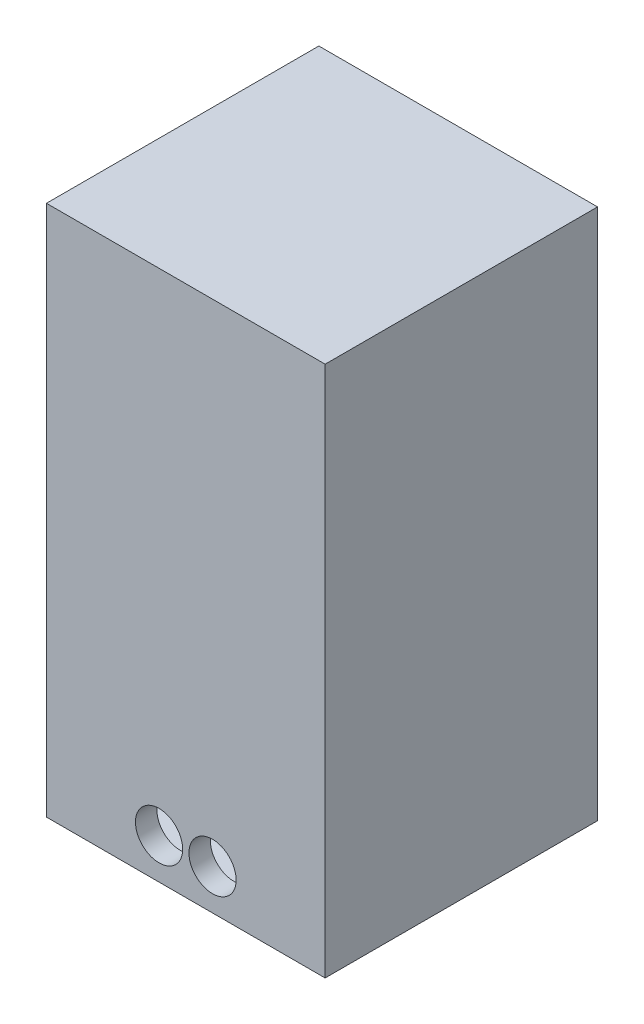
SolidWorks part; units mm, degrees
ref_plane "Front Plane" through (0, 0, 0) normal (0, 0, 1) x (1, 0, 0)
ref_plane "Top Plane" through (0, 0, 0) normal (0, 1, 0) x (1, 0, 0)
ref_plane "Right Plane" through (0, 0, 0) normal (1, 0, 0) x (0, 0, -1)
ref_plane "Plane1" through (0, 0, 433) normal (0, 0, 1) x (1, 0, 0)
sketch "Sketch1" plane through (0, 0, 433) normal (0, 0, 1) x (1, 0, 0)
  line L0 (-443, 1672) -> (-443, -18)
  line L1 (-443, -18) -> (443, -18)
  line L2 (443, -18) -> (443, 1672)
  line L3 (443, 1672) -> (-443, 1672)
  dimension "D1" = 1690
extrude "Boss-Extrude1" add sketch "Sketch1" against normal blind 866
ref_plane "Plane2" through (-425, 0, 0) normal (-1, 0, 0) x (0, -1, 0)
sketch "Sketch2" plane through (-425, 0, 0) normal (-1, 0, 0) x (0, -1, 0)
  line L0 (-7, -415) -> (-7, 415)
  line L1 (-7, 415) -> (-1647, 415)
  line L2 (-1647, 415) -> (-1647, -415)
  line L3 (-1647, -415) -> (-7, -415)
  dimension "D1" = 1640
extrude "Cut-Extrude1" cut sketch "Sketch2" against normal blind 850
sketch "Sketch3" plane through (0, 0, -433) normal (0, 0, -1) x (-1, 0, 0)
  line L0 (-300, 1615) -> (-300, 1605)
  line L1 (-285, 1590) -> (285, 1590)
  line L2 (300, 1605) -> (300, 1615)
  line L3 (285, 1630) -> (-285, 1630)
  arc A0 (-300, 1605) -> (-285, 1590) centre (-285, 1605) ccw
  arc A1 (285, 1590) -> (300, 1605) centre (285, 1605) ccw
  arc A2 (300, 1615) -> (285, 1630) centre (285, 1615) ccw
  arc A3 (-285, 1630) -> (-300, 1615) centre (-285, 1615) ccw
  dimension "D1" = 1590
extrude "Cut-Extrude2" cut sketch "Sketch3" against normal blind 288
sketch "Sketch4" plane through (0, 0, 415) normal (0, 0, -1) x (-1, 0, 0)
  arc A0 (0, 80.4196) -> (0, 139.5804) centre (-85, 110) cw
  arc A1 (0, 139.5804) -> (0, 80.4196) centre (85, 110) cw
extrude "Boss-Extrude2" add sketch "Sketch4" along normal blind 50
hole_wizard "Hole1" positions "Sketch6" profile "Sketch5" legacy
sketch "Sketch6" plane through (0, 0, 365) normal (0, 0, -1) x (-1, 0, 0)
  point P0 (-85, 110)
  point P1 (85, 110)
sketch "Sketch5" plane through (85, 110, 365) normal (1, 0, 0) x (0, 1, 0)
  line L0 (0, 0) -> (0, 68)
  line L1 (0, 68) -> (75, 68)
  line L2 (75, 68) -> (75, 0)
  line L3 (75, 0) -> (0, 0)
  line L4 (0, 110) -> (0, -10) construction
  dimension "Diameter" = 150
  dimension "Depth" = 68
equation "\"box_height\"= 1.69m"
equation "\"D1@Sketch1\"=\"box_height\""
equation "\"D1@Sketch3\"=\"box_height\" - 100mm"
equation "\"D1@Sketch2\"=\"box_height\" - 50mm"
